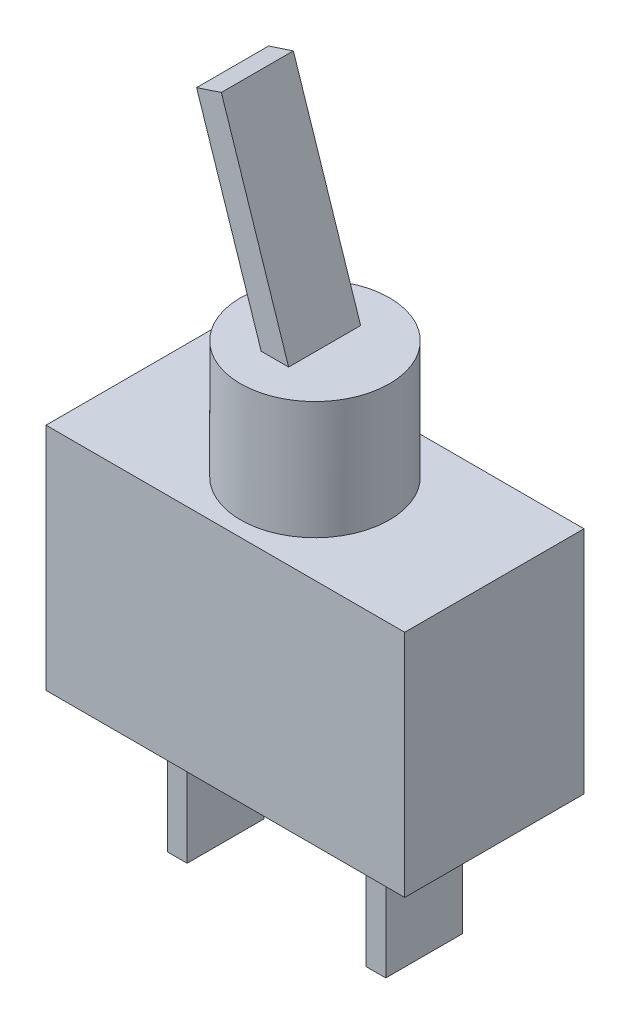
SolidWorks part; units mm, degrees
ref_plane "Front Plane" through (0, 0, 0) normal (0, 0, 1) x (1, 0, 0)
ref_plane "Top Plane" through (0, 0, 0) normal (0, 1, 0) x (1, 0, 0)
ref_plane "Right Plane" through (0, 0, 0) normal (1, 0, 0) x (0, 0, -1)
other "Configuration Table"
sketch "Sketch1" plane through (0, 0, 0) normal (0, 0, 1) x (1, 0, 0)
  line L1 (-14.445, -9.25) -> (14.445, -9.25)
  line L2 (-14.445, -9.25) -> (-14.445, 9.25)
  line L3 (-14.445, 9.25) -> (14.445, 9.25)
  line L4 (14.445, -9.25) -> (14.445, 9.25)
  line L5 (-14.445, -9.25) -> (14.445, 9.25) construction
  line L6 (-14.445, 9.25) -> (14.445, -9.25) construction
  point P0 (0, 0)
extrude "Boss-Extrude1" add sketch "Sketch1" along normal mid plane 14.44
sketch "Sketch2" plane through (0, 0, 0) normal (0, 1, 0) x (1, 0, 0)
  circle A0 centre (0, 0) radius 6
extrude "Boss-Extrude2" add sketch "Sketch2" along normal blind 18.75
sketch "Sketch3" plane through (0, 0, 0) normal (0, 0, 1) x (1, 0, 0)
  line L0 (-0.986, 17.391) -> (0.986, 18.109)
  line L1 (0.986, 18.109) -> (-4.644, 35.199)
  line L2 (-4.644, 35.199) -> (-6.6363, 34.5427)
  line L3 (-6.6363, 34.5427) -> (-0.986, 17.391)
extrude "Boss-Extrude3" add sketch "Sketch3" along normal mid plane 5.8
sketch "Sketch4" plane through (0, 0, 0) normal (0, 0, 1) x (1, 0, 0)
  line L0 (-14.445, -9.25) -> (14.445, -9.25) construction
  line L1 (-8.8, -19.75) -> (-7.2, -19.75)
  line L2 (-8.8, -19.75) -> (-8.8, -9.25)
  line L3 (-8.8, -9.25) -> (-7.2, -9.25)
  line L4 (-7.2, -19.75) -> (-7.2, -9.25)
  line L5 (-8.8, -19.75) -> (-7.2, -9.25) construction
  line L6 (-8.8, -9.25) -> (-7.2, -19.75) construction
  line L14 (7.2, -19.75) -> (8.8, -19.75)
  line L15 (7.2, -19.75) -> (7.2, -9.25)
  line L16 (7.2, -9.25) -> (8.8, -9.25)
  line L17 (8.8, -19.75) -> (8.8, -9.25)
  line L18 (7.2, -19.75) -> (8.8, -9.25) construction
  line L19 (7.2, -9.25) -> (8.8, -19.75) construction
  point P0 (-8, -14.5)
  point P12 (8, -14.5)
extrude "Boss-Extrude4" add sketch "Sketch4" along normal mid plane 6.2
